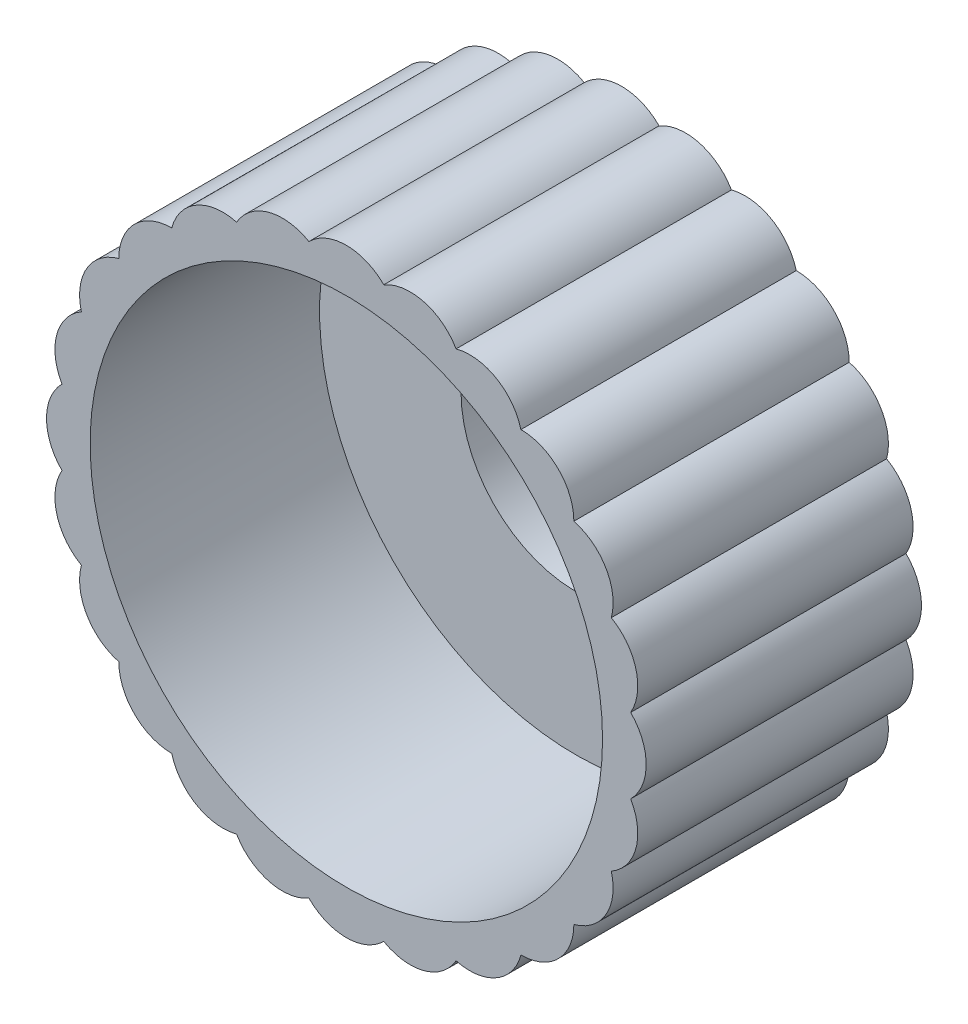
SolidWorks part; units mm, degrees
ref_plane "Front Plane" through (0, 0, 0) normal (0, 0, 1) x (1, 0, 0)
ref_plane "Top Plane" through (0, 0, 0) normal (0, 1, 0) x (1, 0, 0)
ref_plane "Right Plane" through (0, 0, 0) normal (1, 0, 0) x (0, 0, -1)
sketch "Sketch1" plane through (0, 0, 0) normal (0, 0, 1) x (1, 0, 0)
  circle A0 centre (0, 0) radius 18.75
  circle A1 centre (0, 0) radius 16.75
  dimension "D1" = 33.5
  dimension "D2" = 2
extrude "Boss-Extrude1" add sketch "Sketch1" along normal blind 15
sketch "Sketch3" plane through (0, 0, 0) normal (0, 0, -1) x (-1, 0, 0)
  circle A0 centre (0, 0) radius 18.75
  circle A1 centre (0, 0) radius 7.5
  circle A2 centre (0, 0) radius 18.75 construction
  dimension "D1" = 15
extrude "Boss-Extrude2" add sketch "Sketch3" along normal blind 3
sketch "Sketch4" plane through (0, 0, -3) normal (0, 0, -1) x (-1, 0, 0)
  arc A0 (-2.4474, 18.5896) -> (2.4474, 18.5896) centre (0, 16.1422) cw
  circle A1 centre (0, 0) radius 18.75 construction
  arc A2 (2.4474, 18.5896) -> (-2.4474, 18.5896) centre (0, 0) ccw
  point P3 (0, 0)
  point P7 (0, 0)
  point P8 (0, 16.4026)
  dimension "D1" = 15
  dimension "D2" = 90
extrude "Boss-Extrude3" add sketch "Sketch4" against normal up to surface (18 mm away) up to face at (18.75, 0, 15)
pattern_circular "CirPattern1" count 24 over 360 about axis through (0, 0, 0) along (0, 0, 1) of "Boss-Extrude3"
